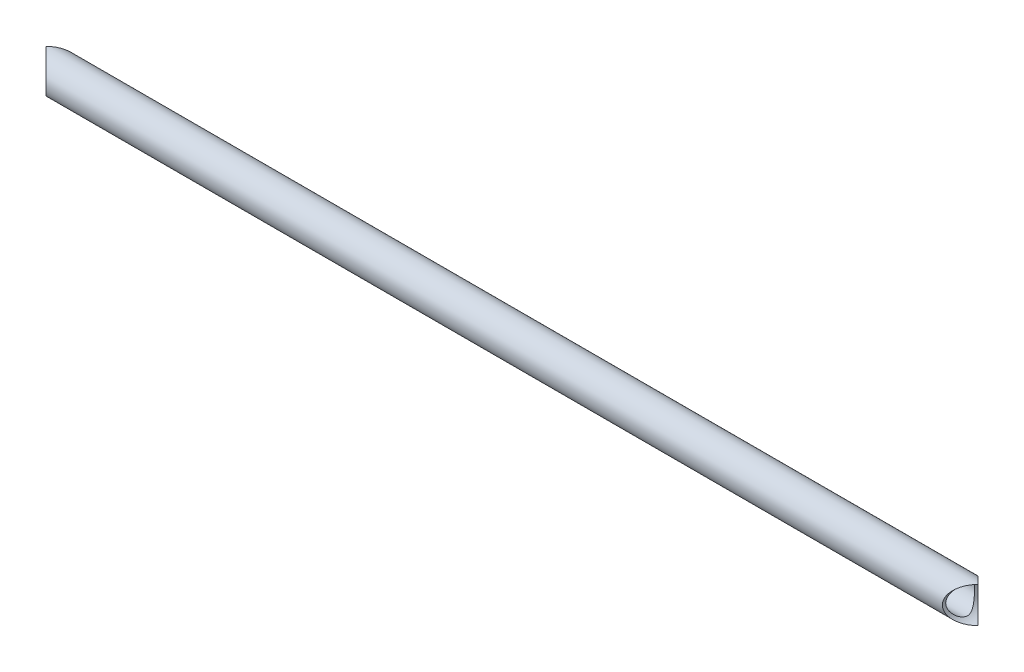
SolidWorks part; units mm, degrees
material "AISI 304"
ref_plane "Plano frontal" through (0, 0, 0) normal (0, 0, 1) x (1, 0, 0)
ref_plane "Plano superior" through (0, 0, 0) normal (0, 1, 0) x (1, 0, 0)
ref_plane "Plano direito" through (0, 0, 0) normal (1, 0, 0) x (0, 0, -1)
ref_plane "Plano1" through (0, 250, 0) normal (0, 1, 0) x (1, 0, 0)
sketch "Esboço1" plane through (0, 0, 0) normal (0, 1, 0) x (1, 0, 0)
  line L0 (0, 162.7552) -> (0, -162.7552)
  line L1 (0, 0) -> (910, 0) construction
  line L2 (910, 265) -> (910, -265) construction
  line L3 (37.1501, 202.6536) -> (910, 265)
  line L4 (37.1501, -202.6536) -> (910, -265)
  arc A0 (0, -162.7552) -> (37.1501, -202.6536) centre (40, -162.7552) ccw
  arc A1 (0, 162.7552) -> (37.1501, 202.6536) centre (40, 162.7552) cw
  point P9 (0, -200)
  point P12 (0, 200)
  dimension "D3" = 40
  dimension "D1" = 400
  dimension "D2" = 910
  dimension "D4" = 530
sketch "Esboço2" plane through (0, 250, 0) normal (0, 1, 0) x (1, 0, 0)
  line L0 (0, 162.7552) -> (0, -162.7552) construction
  line L1 (0, 0) -> (910, 0) construction
  line L2 (910, 265) -> (910, -265) construction
  line L3 (37.1501, 202.6536) -> (910, 265) construction
  line L4 (37.1501, -202.6536) -> (910, -265) construction
  arc A0 (0, -162.7552) -> (37.1501, -202.6536) centre (40, -162.7552) ccw construction
  arc A1 (0, 162.7552) -> (37.1501, 202.6536) centre (40, 162.7552) cw construction
  point P9 (0, -200)
  point P12 (0, 200)
  dimension "D3" = 40
  dimension "D1" = 400
  dimension "D2" = 910
  dimension "D4" = 530
sketch3d "3DSketch1"
  line L0 (37.1501, 0, 202.6536) -> (910, 0, 265) construction
  line L1 (58.5316, 250, 185.1239) -> (58.5316, 250, 204.1808) construction
  line L2 (58.5316, 250, -185.0557) -> (58.5316, 250, -204.1808) construction
  line L3 (0, 250, 0) -> (910, 250, 0) construction
  line L4 (58.5316, 250, -184.1808) -> (58.5316, 250, 184.1808)
  line L7 (58.5316, 250, 185.1239) -> (58.5316, 250, -185.0557) construction
  line L8 (58.5316, 230, 204.1808) -> (58.5316, 0, 204.1808)
  line L11 (58.5316, 230, -204.1808) -> (58.5316, 0, -204.1808)
  line L12 (0, 250, -162.7552) -> (0, 250, 162.7552) construction
  line L14 (37.1501, 0, -202.6536) -> (910, 0, -265) construction
  arc A0 (58.5316, 230, -204.1808) -> (58.5316, 250, -184.1808) centre (58.5316, 230, -184.1808) ccw
  arc A1 (58.5316, 230, 204.1808) -> (58.5316, 250, 184.1808) centre (58.5316, 230, 184.1808) ccw
  circle A2 centre (58.5316, 250, 0) radius 7.9375
  point P5 (58.5316, 250, -204.1808)
  point P7 (78.5316, 230, -184.1808)
  point P11 (58.5316, 250, 204.1808)
  point P13 (38.5316, 230, 184.1808)
  point P15 (58.5316, 250, 7.9375)
  point P17 (37.1501, 0, -202.6536)
  point P18 (87.0231, 0, -206.2159)
  point P34 (196.7435, 15.88, -214.0531)
  dimension "D2" = 20
  dimension "D3" = 15.875
  dimension "D13" = 58.5316
sketch "Esboço4" plane through (0, 250, 0) normal (0, 1, 0) x (1, 0, 0)
  line L0 (60.0173, 204.287) -> (60.0173, -204.287) construction
  line L1 (37.1501, 202.6536) -> (910, 265) construction
  line L2 (0, 200) -> (0, -200) construction
  line L3 (0, -200) -> (910, -265) construction
  line L4 (0, 0) -> (910, 0) construction
  line L5 (910, -265) -> (910, 265) construction
  line L6 (910, 265) -> (0, 200) construction
  point P3 (60.0173, 0)
sketch "Esboço6" plane through (0, 0, 0) normal (0, 0, 1) x (1, 0, 0)
  circle A0 centre (0, 0) radius 7.9375
sketch3d "3DSketch2"
  line L0 (473.5751, 0, 233.8268) -> (473.5751, 230, 233.8268)
  line L1 (37.1501, 0, 202.6536) -> (910, 0, 265) construction
  line L2 (37.1501, 250, 202.6536) -> (910, 250, 265) construction
  line L3 (473.5751, 250, 213.8268) -> (473.5751, 250, -213.8268)
  line L4 (37.1501, 250, -202.6536) -> (910, 250, -265) construction
  line L5 (473.5751, 230, -233.8268) -> (473.5751, 0, -233.8268)
  line L6 (37.1501, 0, -202.6536) -> (910, 0, -265) construction
  arc A0 (473.5751, 250, -213.8268) -> (473.5751, 230, -233.8268) centre (473.5751, 230, -213.8268) ccw
  arc A1 (473.5751, 230, 233.8268) -> (473.5751, 250, 213.8268) centre (473.5751, 230, 213.8268) ccw
  point P14 (473.5751, 250, -233.8268)
  point P15 (453.5751, 230, -213.8268)
  point P18 (473.5751, 250, 233.8268)
  point P19 (453.5751, 230, 213.8268)
  dimension "D1" = 20
sketch "Esboço7" plane through (0, 250, 0) normal (0, 1, 0) x (1, 0, 0)
  line L0 (58.5316, 150) -> (473.5751, 150)
  line L1 (58.5316, 184.1808) -> (58.5316, -184.1808) construction
  line L2 (473.5751, -213.8268) -> (473.5751, 213.8268) construction
  line L3 (0, 0) -> (910, 0) construction
  dimension "D1" = 150
other "Pipe - configured 21.3 X 2.3(3)"
ref_plane "Plano2" through (58.5316, 250, -150) normal (1, 0, 0) x (0, 0, -1)
sketch "Sketch1" plane through (58.5316, 250, -150) normal (1, 0, 0) x (0, 0, -1)
  circle A0 centre (0, 0) radius 6.4375
  circle A1 centre (0, 0) radius 7.9375
  point P3 (0, 0)
  dimension "Out_dia" = 15.875
  dimension "D1" = 1.5
sketch "Esboço10" plane through (0, 0, 0) normal (0, 0, 1) x (1, 0, 0)
  line L0 (473.5751, 257.9375) -> (58.5316, 257.9375) construction
  circle A0 centre (58.5316, 250) radius 7.9375
extrude "Corte-extrusão1" cut sketch "Esboço10" against normal through all both and the other way through all
sketch "Esboço11" plane through (0, 0, 0) normal (0, 0, 1) x (1, 0, 0)
  line L0 (473.5751, 257.9375) -> (58.5316, 257.9375) construction
  circle A0 centre (473.5751, 250) radius 7.9375
extrude "Corte-extrusão2" cut sketch "Esboço11" against normal through all both and the other way through all
